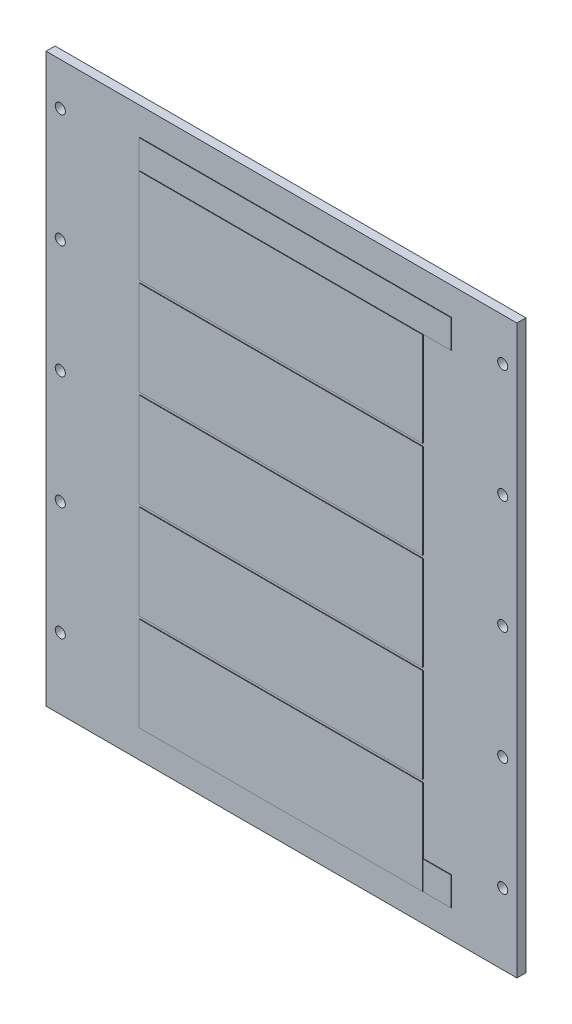
SolidWorks part; units mm, degrees
ref_plane "Front Plane" through (0, 0, 0) normal (0, 0, 1) x (1, 0, 0)
ref_plane "Top Plane" through (0, 0, 0) normal (0, 1, 0) x (1, 0, 0)
ref_plane "Right Plane" through (0, 0, 0) normal (1, 0, 0) x (0, 0, -1)
sketch "Sketch1" plane through (0, 0, 0) normal (0, 0, 1) x (1, 0, 0)
  line L1 (-41.5, -50) -> (41.5, -50)
  line L2 (-41.5, -50) -> (-41.5, 50)
  line L3 (-41.5, 50) -> (41.5, 50)
  line L4 (41.5, -50) -> (41.5, 50)
  line L5 (-41.5, -50) -> (41.5, 50) construction
  line L6 (-41.5, 50) -> (41.5, -50) construction
  point P0 (0, 0)
  dimension "D1" = 83
  dimension "D2" = 100
extrude "Boss-Extrude1" add sketch "Sketch1" along normal blind 1.5875
sketch "Sketch2" plane through (0, 0, 1.5875) normal (0, 0, 1) x (1, 0, 0)
  line L0 (-35, 45) -> (35, 45)
  line L1 (35, 45) -> (37.5, 42.5)
  line L2 (37.5, 42.5) -> (37.5, 30.5)
  line L3 (35, 28) -> (-35, 28)
  line L4 (-37.5, 30.5) -> (-37.5, 42.5)
  line L5 (-37.5, 42.5) -> (-35, 45)
  line L6 (0, 0) -> (0, 50) construction
  line L7 (41.5, 50) -> (-41.5, 50) construction
  line L8 (-35, 28) -> (-37.5, 30.5)
  line L9 (37.5, 30.5) -> (35, 28)
  line L10 (-35, 26.75) -> (35, 26.75)
  line L11 (35, 26.75) -> (37.5, 24.25)
  line L12 (37.5, 24.25) -> (37.5, 12.25)
  line L13 (35, 9.75) -> (-35, 9.75)
  line L14 (-37.5, 12.25) -> (-37.5, 24.25)
  line L15 (-37.5, 24.25) -> (-35, 26.75)
  line L16 (-35, 9.75) -> (-37.5, 12.25)
  line L17 (37.5, 12.25) -> (35, 9.75)
  line L18 (-35, 8.5) -> (35, 8.5)
  line L19 (35, 8.5) -> (37.5, 6)
  line L20 (37.5, 6) -> (37.5, -6)
  line L21 (35, -8.5) -> (-35, -8.5)
  line L22 (-37.5, -6) -> (-37.5, 6)
  line L23 (-37.5, 6) -> (-35, 8.5)
  line L24 (-35, -8.5) -> (-37.5, -6)
  line L25 (37.5, -6) -> (35, -8.5)
  line L26 (-35, -9.75) -> (35, -9.75)
  line L27 (35, -9.75) -> (37.5, -12.25)
  line L28 (37.5, -12.25) -> (37.5, -24.25)
  line L29 (35, -26.75) -> (-35, -26.75)
  line L30 (-37.5, -24.25) -> (-37.5, -12.25)
  line L31 (-37.5, -12.25) -> (-35, -9.75)
  line L32 (-35, -26.75) -> (-37.5, -24.25)
  line L33 (37.5, -24.25) -> (35, -26.75)
  line L34 (-35, -28) -> (35, -28)
  line L35 (35, -28) -> (37.5, -30.5)
  line L36 (37.5, -30.5) -> (37.5, -42.5)
  line L37 (35, -45) -> (-35, -45)
  line L38 (-37.5, -42.5) -> (-37.5, -30.5)
  line L39 (-37.5, -30.5) -> (-35, -28)
  line L40 (-35, -45) -> (-37.5, -42.5)
  line L41 (37.5, -42.5) -> (35, -45)
  line L42 (-41.5, -50) -> (41.5, -50) construction
  point P4 (37.5, 28)
  point P5 (-37.5, 28)
  point P20 (37.5, 9.75)
  point P21 (-37.5, 9.75)
  point P30 (37.5, -8.5)
  point P31 (-37.5, -8.5)
  point P40 (37.5, -26.75)
  point P41 (-37.5, -26.75)
  point P50 (37.5, -45)
  point P51 (-37.5, -45)
  dimension "D1" = 75
  dimension "D2" = 2.5
  dimension "D3" = 45
  dimension "D4" = 17
  dimension "D5" = 5
  dimension "D7" = 5
  dimension "D6" = 5
extrude "Boss-Extrude2" [suppressed] add sketch "Sketch2" along normal blind 0.25
hole_wizard "#0 Clearance Hole1" positions "Sketch4" profile "Sketch3" hole size "#0" standard "ANSI Inch"
sketch "Sketch4" plane through (0, 0, 1.5875) normal (0, 0, 1) x (1, 0, 0)
  line L0 (-41.5, 50) -> (-41.5, -50) construction
  line L1 (41.5, 50) -> (-41.5, 50) construction
  line L2 (-41.5, -50) -> (41.5, -50) construction
  line L3 (0, 50) -> (0, -50) construction
  point P56 (-39, 42.5)
  point P79 (-39, 22.5)
  point P80 (-39, 2.5)
  point P81 (-39, -17.5)
  point P82 (-39, -37.5)
  point P92 (39, -37.5)
  point P93 (39, -17.5)
  point P94 (39, 2.5)
  point P95 (39, 22.5)
  point P96 (39, 42.5)
  dimension "D1" = 2.5
  dimension "D2" = 7.5
  dimension "D3" = 5
  dimension "D4" = 20
sketch "Sketch3" plane through (-39, 42.5, 1.5875) normal (1, 0, 0) x (0, -1, 0)
  line L0 (0, 0) -> (0, 3.7092)
  line L1 (0, 3.7092) -> (0.889, 3.175)
  line L2 (0.889, 3.175) -> (0.889, 0)
  line L5 (0.889, 0) -> (0, 0)
  line L10 (0, 3.7092) -> (-0.889, 3.175) construction
  line L11 (0, -6.35) -> (0, 107.95) construction
  dimension "Hole Dia." = 1.778
  dimension "Hole Depth" = 3.175
  dimension "Drill Angle" = 118
sketch "Sketch5" plane through (0, 0, 1.5875) normal (0, 0, 1) x (1, 0, 0)
  line L0 (-25, 22.9) -> (25, 22.9)
  line L1 (-25, 40) -> (25, 40)
  line L2 (-25, 40) -> (-25, 23.4)
  line L3 (-25, 23.4) -> (25, 23.4)
  line L4 (25, 40) -> (25, 23.4)
  line L5 (-25, 22.9) -> (-25, 6.3)
  line L6 (-25, 6.3) -> (25, 6.3)
  line L7 (25, 22.9) -> (25, 6.3)
  line L8 (-25, 5.8) -> (25, 5.8)
  line L9 (-25, 5.8) -> (-25, -10.8)
  line L10 (-25, -10.8) -> (25, -10.8)
  line L11 (25, 5.8) -> (25, -10.8)
  line L12 (-25, -11.3) -> (25, -11.3)
  line L13 (-25, -11.3) -> (-25, -27.9)
  line L14 (-25, -27.9) -> (25, -27.9)
  line L15 (25, -11.3) -> (25, -27.9)
  line L17 (-25, -28.4) -> (25, -28.4)
  line L18 (-25, -28.4) -> (-25, -45)
  line L19 (-25, -45) -> (25, -45)
  line L20 (25, -28.4) -> (25, -45)
  line L21 (-41.5, -50) -> (41.5, -50) construction
  line L22 (0, 0) -> (0, -10.8) construction
  dimension "D1" = 85
  dimension "D2" = 50
  dimension "D4" = 0.5
  dimension "D5" = 5
  dimension "D3" = 5
extrude "Boss-Extrude3" add sketch "Sketch5" along normal blind 0.1
sketch "Sketch6" plane through (0, 0, 1.5875) normal (0, 0, 1) x (1, 0, 0)
  line L0 (25, 40) -> (-25, 40) construction
  line L1 (-25, 40.1) -> (30, 40.1)
  line L2 (-25, 40.1) -> (-25, 45.1)
  line L3 (-25, 45.1) -> (30, 45.1)
  line L4 (30, 40.1) -> (30, 45.1)
  line L5 (-25, 40) -> (-25, 23.4) construction
  dimension "D1" = 5
  dimension "D2" = 55
  dimension "D3" = 0.1
extrude "Boss-Extrude4" add sketch "Sketch6" along normal blind 0.1
sketch "Sketch7" plane through (0, 0, 1.5875) normal (0, 0, 1) x (1, 0, 0)
  line L0 (30, 40.1) -> (30, 45.1) construction
  line L1 (25.01, -45) -> (30, -45)
  line L2 (25.01, -45) -> (25.01, -40)
  line L3 (25.01, -40) -> (30, -40)
  line L4 (30, -45) -> (30, -40)
  line L5 (25, -45) -> (25, -28.4) construction
  line L6 (-25, -45) -> (25, -45) construction
  dimension "D1" = 0.01
extrude "Boss-Extrude5" add sketch "Sketch7" along normal blind 0.1
